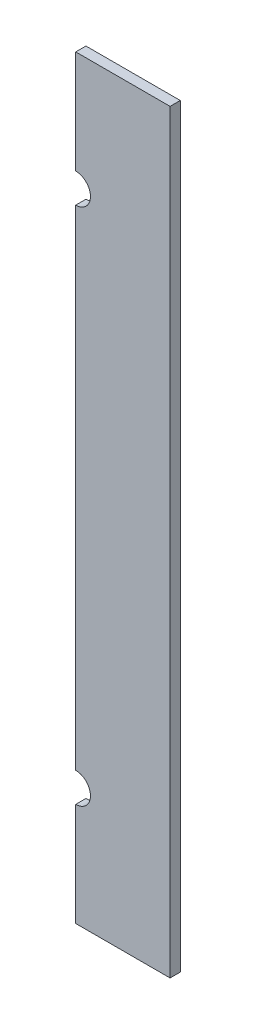
SolidWorks part; units mm, degrees
material "AISI 1020 Steel, Cold Rolled"
ref_plane "Front Plane" through (0, 0, 0) normal (0, 0, 1) x (1, 0, 0)
ref_plane "Top Plane" through (0, 0, 0) normal (0, 1, 0) x (1, 0, 0)
ref_plane "Right Plane" through (0, 0, 0) normal (1, 0, 0) x (0, 0, -1)
sketch "Sketch1" plane through (0, 0, 0) normal (0, 1, 0) x (1, 0, 0)
  line L1 (0, 0) -> (25.4, 0)
  line L2 (0, 0) -> (0, -2.7432)
  line L3 (0, -2.7432) -> (25.4, -2.7432)
  line L4 (25.4, 0) -> (25.4, -2.7432)
  dimension "D1" = 25.4
  dimension "D2" = 2.7432
extrude "Boss-Extrude1" add sketch "Sketch1" along normal blind 203.2
extrude "Cut-Extrude1" cut sketch "Sketch2" against normal through all and the other way through all
sketch "Sketch2" plane through (-3.9083, 106.6067, 5.9182) normal (0, 0, 1) x (1, 0, 0)
  line L0 (360.1647, 83.8933) -> (360.1647, -93.9067) construction
  line L6 (347.4647, -5.0067) -> (371.2772, -5.0067) construction
  line L8 (3.9083, 83.8933) -> (3.9083, -93.9067) construction
  line L11 (-310.6722, 83.8933) -> (-310.6722, -93.9067) construction
  circle A0 centre (360.1647, 64.8433) radius 3.9688
  circle A1 centre (360.1647, -74.8567) radius 3.9688
  circle A3 centre (3.9083, 64.8433) radius 3.9687
  circle A4 centre (-310.6722, 64.8433) radius 3.9688
  circle A5 centre (3.9083, -74.8567) radius 3.9687
  circle A6 centre (-310.6722, -74.8567) radius 3.9688
